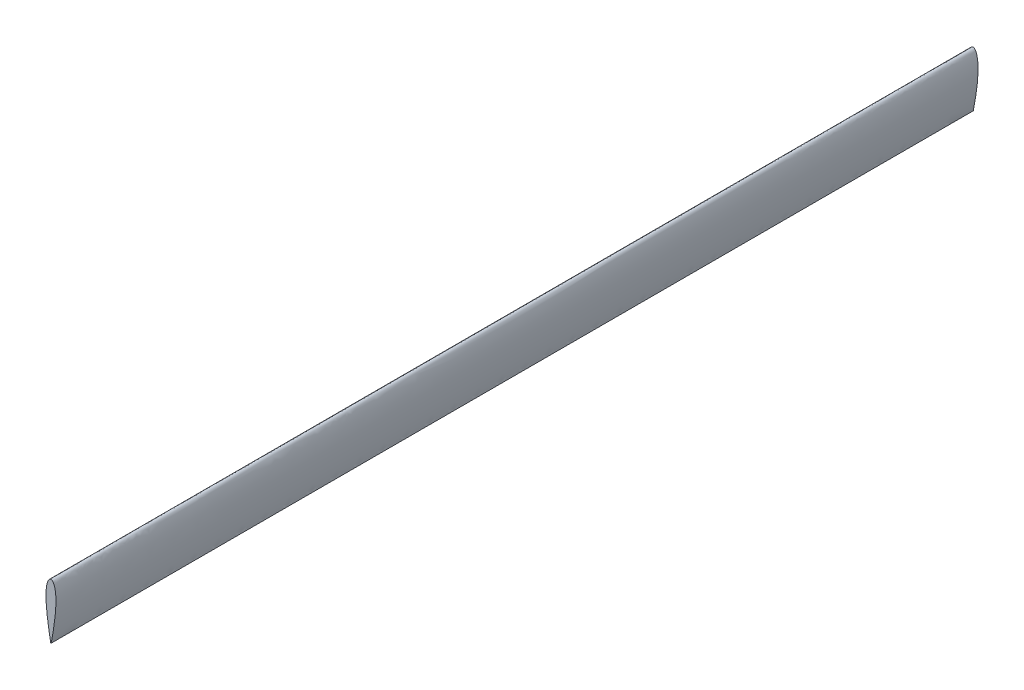
SolidWorks part; units mm, degrees
ref_plane "Front Plane" through (0, 0, 0) normal (0, 0, 1) x (1, 0, 0)
ref_plane "Top Plane" through (0, 0, 0) normal (0, 1, 0) x (1, 0, 0)
ref_plane "Right Plane" through (0, 0, 0) normal (1, 0, 0) x (0, 0, -1)
sketch "Sketch1" plane through (0, 0, 0) normal (0, 0, 1) x (1, 0, 0)
  spline S0 degree 3 poles (-66.5792, -64.8534) (-67.4876, -64.3755) (-68.396, -64.8534) (-68.9509, -65.6909) (-69.4058, -66.7768) (-69.7611, -68.1644) (-70.0166, -69.8247) (-70.1632, -71.7203) (-70.1985, -73.8056) (-70.1328, -76.0297) (-69.9786, -78.3385) (-69.7555, -80.6754) (-69.4826, -82.9832) (-69.1801, -85.2052) (-68.8646, -87.2877) (-68.5501, -89.1754) (-68.2669, -90.8353) (-67.9857, -92.1866) (-67.8345, -93.302) (-67.5668, -93.9084) (-67.6648, -94.4853) (-67.3104, -94.4853) (-67.4085, -93.9084) (-67.1402, -93.302) (-66.9928, -92.1861) (-66.6905, -90.8381) (-66.5103, -89.1613) (-66.0523, -87.2971) (-65.9465, -85.1841) (-65.4495, -82.9907) (-65.2316, -80.6736) (-64.9934, -78.3389) (-64.8432, -76.0296) (-64.7765, -73.8056) (-64.8121, -71.7203) (-64.9585, -69.8247) (-65.2141, -68.1644) (-65.5694, -66.7768) (-66.0243, -65.6909) (-66.5792, -64.8534) (-67.4876, -64.3755) (-68.396, -64.8534) knots -0.048226 -0.029477 -0.014809 0 0.014809 0.029477 0.048226 0.07128 0.098404 0.129148 0.162903 0.19894 0.23643 0.274476 0.312144 0.348498 0.382632 0.413689 0.440888 0.463542 0.481066 0.493014 0.499065 0.500894 0.506946 0.518894 0.536418 0.559072 0.586273 0.617337 0.651456 0.687856 0.725524 0.76357 0.80106 0.837097 0.870852 0.901596 0.92872 0.951774 0.970523 0.985191 1 1.014809 1.029477 1.048226 only from (-67.4876, -64.5353) to (-67.4876, -64.5353)
extrude "Boss-Extrude1" add sketch "Sketch1" along normal blind 500
